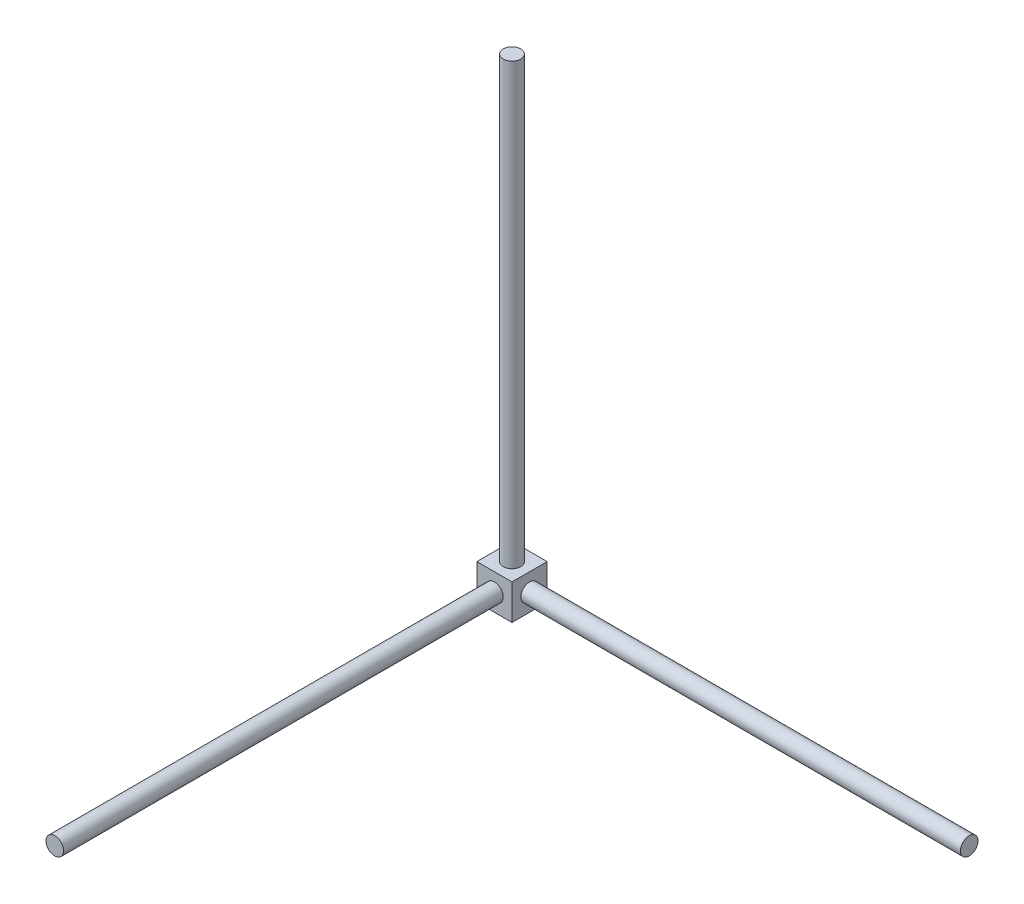
SolidWorks part; units mm, degrees
ref_plane "Front Plane" through (0, 0, 0) normal (0, 0, 1) x (1, 0, 0)
ref_plane "Top Plane" through (0, 0, 0) normal (0, 1, 0) x (1, 0, 0)
ref_plane "Right Plane" through (0, 0, 0) normal (1, 0, 0) x (0, 0, -1)
sketch "Sketch1" plane through (0, 0, 0) normal (0, 1, 0) x (1, 0, 0)
  line L1 (10, 10) -> (-10, 10)
  line L2 (10, 10) -> (10, -10)
  line L3 (10, -10) -> (-10, -10)
  line L4 (-10, 10) -> (-10, -10)
  line L5 (10, 10) -> (-10, -10) construction
  line L6 (10, -10) -> (-10, 10) construction
  point P0 (0, 0)
  dimension "D1" = 20
extrude "Boss-Extrude1" add sketch "Sketch1" along normal mid plane 20
sketch "Sketch2" plane through (10, 0, 0) normal (1, 0, 0) x (0, 0, -1)
  circle A0 centre (0, 0) radius 5
  dimension "D1" = 10
extrude "Boss-Extrude2" add sketch "Sketch2" along normal blind 250
sketch "Sketch3" plane through (0, 0, 10) normal (0, 0, 1) x (1, 0, 0)
  circle A0 centre (0, 0) radius 5
  dimension "D1" = 10
extrude "Boss-Extrude3" add sketch "Sketch3" along normal blind 250
sketch "Sketch4" plane through (0, 10, 0) normal (0, 1, 0) x (1, 0, 0)
  circle A0 centre (0, 0) radius 5
  dimension "D1" = 10
extrude "Boss-Extrude4" add sketch "Sketch4" along normal blind 250
